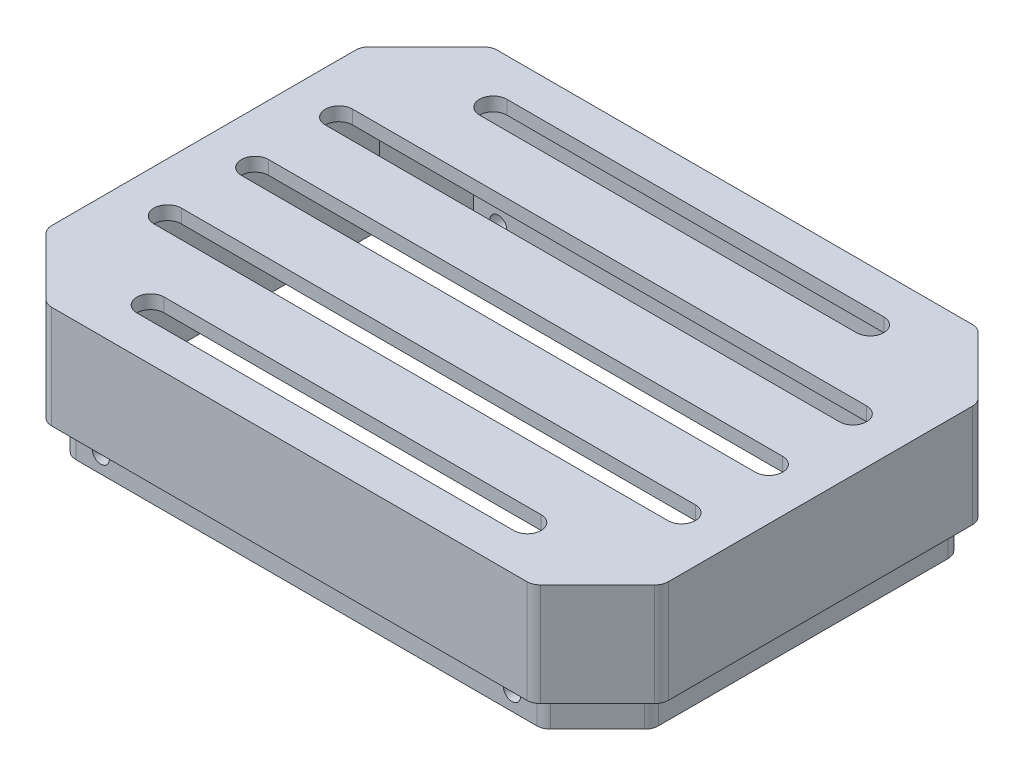
SolidWorks part; units mm, degrees
ref_plane "Front Plane" through (0, 0, 0) normal (0, 0, 1) x (1, 0, 0)
ref_plane "Top Plane" through (0, 0, 0) normal (0, 1, 0) x (1, 0, 0)
ref_plane "Right Plane" through (0, 0, 0) normal (1, 0, 0) x (0, 0, -1)
sketch "Sketch1" plane through (0, 0, 0) normal (0, 1, 0) x (1, 0, 0)
  line L0 (-45.085, -41.275) -> (-57.15, -29.21)
  line L1 (-45.085, 41.275) -> (45.085, 41.275)
  line L2 (-57.15, 29.21) -> (-57.15, -29.21)
  line L3 (-45.085, -41.275) -> (45.085, -41.275)
  line L4 (57.15, 29.21) -> (57.15, -29.21)
  line L5 (-51.1175, 35.2425) -> (51.1175, -35.2425) construction
  line L6 (-51.1175, -35.2425) -> (51.1175, 35.2425) construction
  line L7 (-57.15, 29.21) -> (-45.085, 41.275)
  line L8 (45.085, 41.275) -> (57.15, 29.21)
  line L9 (45.085, -41.275) -> (57.15, -29.21)
  point P0 (0, 0)
  point P1 (-48.6403, -46.3082)
  point P15 (-51.1175, -35.2425)
  point P16 (-55.6365, 39.8117)
  point P17 (-51.1175, 35.2425)
  point P18 (43.643, 44.6424)
  point P19 (51.1175, 35.2425)
  point P20 (31.8161, -50.4726)
  point P21 (40.478, -40.1449)
  point P22 (51.1175, -35.2425)
  point P23 (52.9712, -43.766)
  point P24 (-57.15, -31.177)
  dimension "D1" = 90.17
  dimension "D2" = 135
  dimension "D3" = 114.3
  dimension "D4" = 82.55
  dimension "D5" = 58.42
extrude "Boss-Extrude1" add sketch "Sketch1" along normal blind 25.4
sketch "Sketch2" plane through (0, 0, 0) normal (0, -1, 0) x (1, 0, 0)
  line L0 (-53.975, 27.8949) -> (-53.975, -27.8949)
  line L1 (-53.975, -27.8949) -> (-43.7699, -38.1)
  line L2 (-43.7699, -38.1) -> (43.7699, -38.1)
  line L3 (43.7699, -38.1) -> (53.975, -27.8949)
  line L4 (53.975, -27.8949) -> (53.975, 27.8949)
  line L5 (53.975, 27.8949) -> (43.7699, 38.1)
  line L6 (43.7699, 38.1) -> (-43.7699, 38.1)
  line L7 (-43.7699, 38.1) -> (-53.975, 27.8949)
  line L8 (-57.15, -29.21) -> (-57.15, 29.21) construction
  line L9 (-45.085, 41.275) -> (45.085, 41.275) construction
  line L10 (57.15, 29.21) -> (57.15, -29.21) construction
  line L11 (45.085, -41.275) -> (-45.085, -41.275) construction
  line L12 (-57.15, 29.21) -> (-45.085, 41.275) construction
  line L13 (-45.085, -41.275) -> (-57.15, -29.21) construction
  line L14 (57.15, -29.21) -> (45.085, -41.275) construction
  line L15 (45.085, 41.275) -> (57.15, 29.21) construction
  line L16 (-57.15, 29.21) -> (-57.15, -29.21)
  line L17 (-57.15, -29.21) -> (-45.085, -41.275)
  line L18 (-45.085, -41.275) -> (45.085, -41.275)
  line L19 (45.085, -41.275) -> (57.15, -29.21)
  line L20 (57.15, -29.21) -> (57.15, 29.21)
  line L21 (57.15, 29.21) -> (45.085, 41.275)
  line L22 (45.085, 41.275) -> (-45.085, 41.275)
  line L23 (-45.085, 41.275) -> (-57.15, 29.21)
  dimension "D1" = 3.175
  dimension "D2" = 3.175
  dimension "D3" = 3.175
  dimension "D4" = 3.175
  dimension "D5" = 3.175
  dimension "D6" = 3.175
  dimension "D7" = 3.175
  dimension "D8" = 3.175
extrude "Cut-Extrude1" cut sketch "Sketch2" against normal blind 6.35
sketch "Sketch3" plane through (0, 0, 0) normal (0, -1, 0) x (1, 0, 0)
  line L0 (-51.435, 26.8428) -> (-51.435, -26.8428)
  line L1 (-51.435, -26.8428) -> (-42.7178, -35.56)
  line L2 (-42.7178, -35.56) -> (42.7178, -35.56)
  line L3 (42.7178, -35.56) -> (51.435, -26.8428)
  line L4 (51.435, -26.8428) -> (51.435, 26.8428)
  line L5 (51.435, 26.8428) -> (42.7178, 35.56)
  line L6 (42.7178, 35.56) -> (-42.7178, 35.56)
  line L7 (-42.7178, 35.56) -> (-51.435, 26.8428)
  line L8 (-43.7699, 38.1) -> (-53.975, 27.8949) construction
  line L9 (-53.975, -27.8949) -> (-43.7699, -38.1) construction
  line L10 (43.7699, -38.1) -> (53.975, -27.8949) construction
  line L11 (53.975, 27.8949) -> (43.7699, 38.1) construction
  line L12 (43.7699, 38.1) -> (-43.7699, 38.1) construction
  line L13 (-53.975, 27.8949) -> (-53.975, -27.8949) construction
  line L14 (-43.7699, -38.1) -> (43.7699, -38.1) construction
  line L15 (53.975, -27.8949) -> (53.975, 27.8949) construction
  dimension "D1" = 2.54
  dimension "D2" = 2.54
  dimension "D3" = 2.54
  dimension "D4" = 2.54
  dimension "D5" = 2.54
  dimension "D6" = 2.54
  dimension "D7" = 2.54
  dimension "D8" = 2.54
extrude "Cut-Extrude2" cut sketch "Sketch3" against normal blind 22.86
sketch "Sketch4" plane through (0, 0, 38.1) normal (0, 0, 1) x (1, 0, 0)
  line L0 (-38.1, 3.175) -> (38.1, 3.175) construction
  line L1 (0, 3.175) -> (0, 0) construction
  line L2 (43.7699, 0) -> (-43.7699, 0) construction
  circle A0 centre (-38.1, 3.175) radius 1.575
  circle A1 centre (38.1, 3.175) radius 1.575
  dimension "D3" = 3.15
  dimension "D1" = 3.175
  dimension "D2" = 76.2
extrude "Cut-Extrude3" cut sketch "Sketch4" against normal through all
sketch "Sketch5" plane through (0, 25.4, 0) normal (0, 1, 0) x (1, 0, 0)
  line L0 (-0.3149, 0) -> (-0.3149, 31.75) construction
  line L2 (-35.2399, 31.75) -> (34.6101, 31.75) construction
  line L3 (-35.2399, -31.75) -> (34.6101, -31.75) construction
  line L4 (-35.2399, 31.75) -> (34.6101, 31.75) construction
  line L5 (-35.2399, 34.29) -> (34.6101, 34.29)
  line L6 (-35.2399, 29.21) -> (34.6101, 29.21)
  line L7 (-47.625, 0) -> (47.625, 0) construction
  line L8 (-47.625, 2.54) -> (47.625, 2.54)
  line L9 (-47.625, -2.54) -> (47.625, -2.54)
  line L10 (-35.2399, -31.75) -> (34.6101, -31.75) construction
  line L11 (-35.2399, -29.21) -> (34.6101, -29.21)
  line L12 (-35.2399, -34.29) -> (34.6101, -34.29)
  line L13 (-47.9399, 15.875) -> (47.3101, 15.875) construction
  line L14 (-47.9399, -15.875) -> (47.3101, -15.875) construction
  line L15 (-47.9399, -15.875) -> (47.3101, -15.875) construction
  line L16 (-47.9399, -13.335) -> (47.3101, -13.335)
  line L17 (-47.9399, -18.415) -> (47.3101, -18.415)
  line L18 (-47.9399, 15.875) -> (47.3101, 15.875) construction
  line L19 (-47.9399, 18.415) -> (47.3101, 18.415)
  line L20 (-47.9399, 13.335) -> (47.3101, 13.335)
  line L21 (-0.3149, 0) -> (-0.3149, -31.75) construction
  arc A0 (-35.2399, 34.29) -> (-35.2399, 29.21) centre (-35.2399, 31.75) ccw
  arc A1 (34.6101, 29.21) -> (34.6101, 34.29) centre (34.6101, 31.75) ccw
  arc A2 (-47.625, 2.54) -> (-47.625, -2.54) centre (-47.625, 0) ccw
  arc A3 (47.625, -2.54) -> (47.625, 2.54) centre (47.625, 0) ccw
  arc A4 (-35.2399, -29.21) -> (-35.2399, -34.29) centre (-35.2399, -31.75) ccw
  arc A5 (34.6101, -34.29) -> (34.6101, -29.21) centre (34.6101, -31.75) ccw
  arc A6 (-47.9399, -13.335) -> (-47.9399, -18.415) centre (-47.9399, -15.875) ccw
  arc A7 (47.3101, -18.415) -> (47.3101, -13.335) centre (47.3101, -15.875) ccw
  arc A8 (-47.9399, 18.415) -> (-47.9399, 13.335) centre (-47.9399, 15.875) ccw
  arc A9 (47.3101, 13.335) -> (47.3101, 18.415) centre (47.3101, 15.875) ccw
  point P0 (-0.3149, 31.75)
  point P2 (-2.8128, 29.6424)
  point P3 (-47.3101, -15.875)
  point P4 (0, 0)
  point P7 (-25.4211, -1.7768)
  point P8 (0, 0)
  point P11 (-0.3149, 31.75)
  point P14 (-0.3149, -31.75)
  point P19 (0, 0)
  point P25 (-0.3149, -31.75)
  point P30 (-0.3149, -15.875)
  point P33 (-0.3149, 15.875)
  point P36 (-0.3149, -15.875)
  point P41 (-0.3149, 15.875)
  point P46 (0, 0)
  point P49 (0, 0)
  point P50 (-0.3149, -15.875)
  point P51 (0, 0)
  point P52 (-0.3149, 15.875)
  point P53 (0, -32.0252)
  point P54 (0, 0)
  point P55 (26.0067, -2.54)
  point P56 (-46.3773, 0)
  point P57 (-54.6702, 0)
  point P58 (0, 0)
  dimension "D2" = 2.54
  dimension "D1" = 31.75
  dimension "D3" = 69.85
  dimension "D4" = 95.25
extrude "Cut-Extrude4" cut sketch "Sketch5" against normal through all
fillet "Fillet1" radius 2.54 16 edges at (45.085, 15.875, 41.275) (57.15, 15.875, 29.21) (57.15, 15.875, -29.21) (45.085, 15.875, -41.275) (-45.085, 15.875, -41.275) (-57.15, 15.875, -29.21) (-57.15, 15.875, 29.21) (-45.085, 15.875, 41.275) (43.7699, 3.175, 38.1) (53.975, 3.175, 27.8949) (53.975, 3.175, -27.8949) (43.7699, 3.175, -38.1) (-53.975, 3.175, -27.8949) (-43.7699, 3.175, -38.1) (-53.975, 3.175, 27.8949) (-43.7699, 3.175, 38.1)
